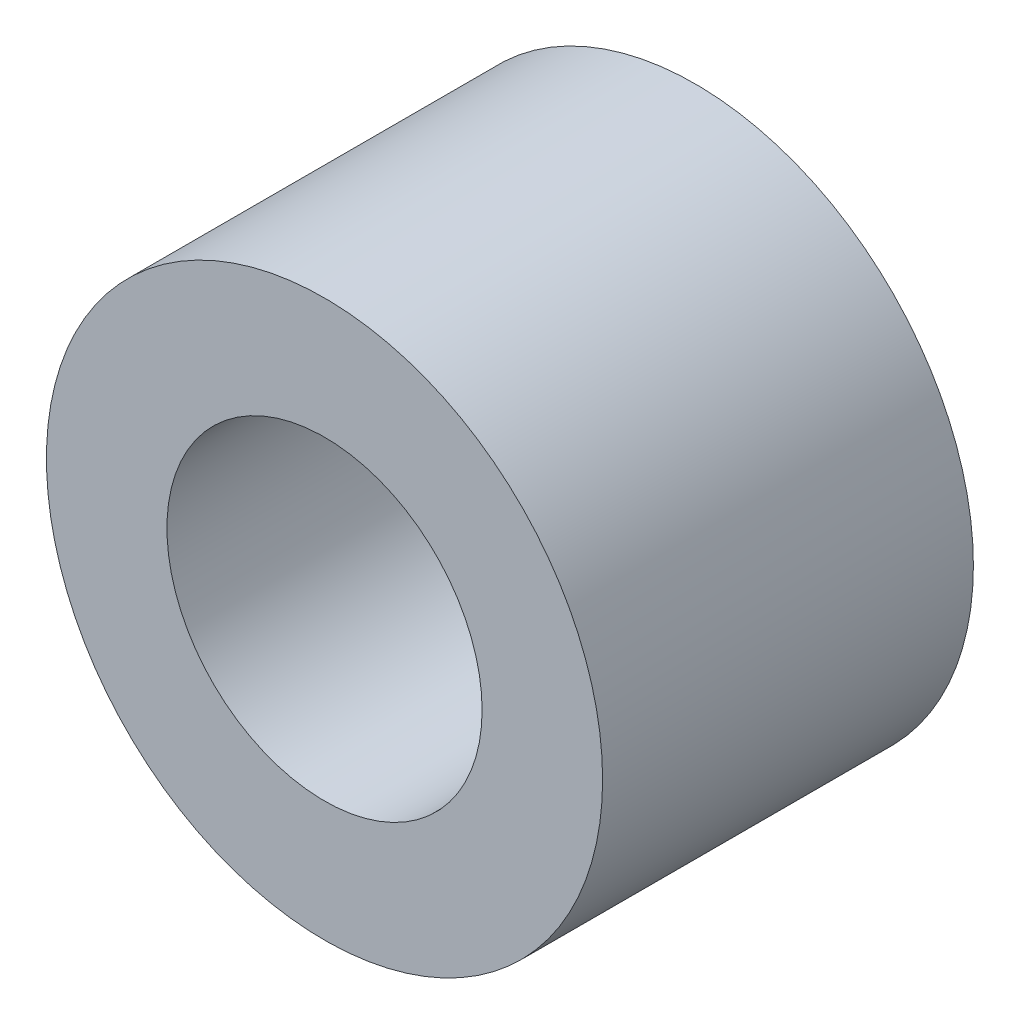
SolidWorks part; units mm, degrees
material "6061-T6 (SS)"
ref_plane "Front Plane" through (0, 0, 0) normal (0, 0, 1) x (1, 0, 0)
ref_plane "Top Plane" through (0, 0, 0) normal (0, 1, 0) x (1, 0, 0)
ref_plane "Right Plane" through (0, 0, 0) normal (1, 0, 0) x (0, 0, -1)
sketch "Sketch1" plane through (0, 0, 0) normal (0, 0, 1) x (1, 0, 0)
  circle A0 centre (0, 0) radius 3
  circle A1 centre (0, 0) radius 1.7
extrude "Spacer" add sketch "Sketch1" along normal blind 4
